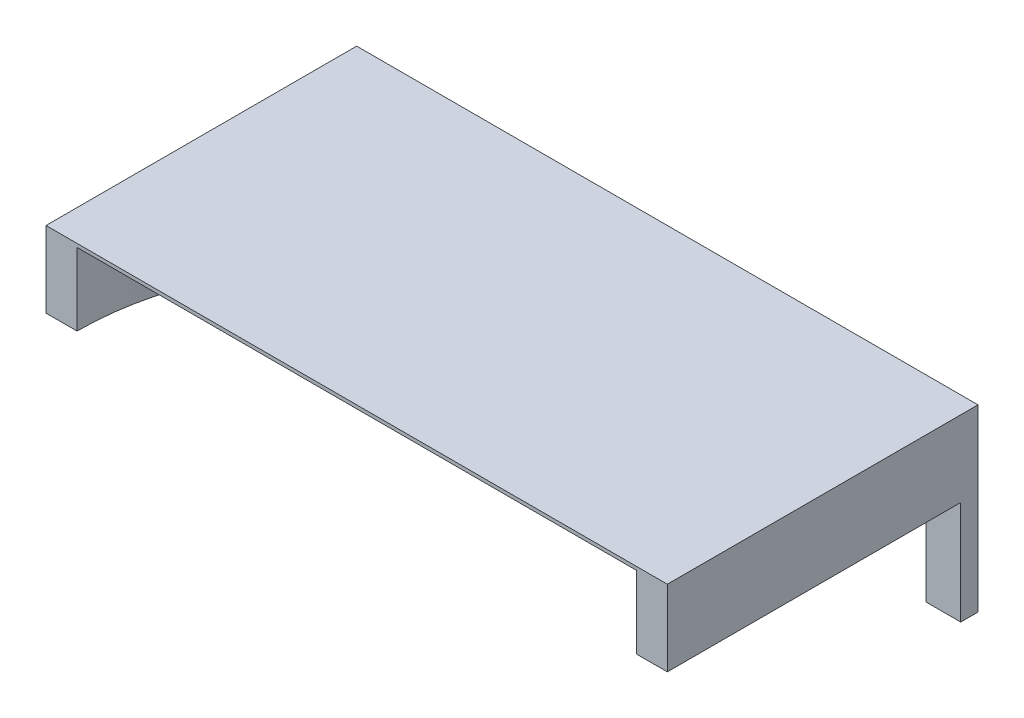
SolidWorks part; units mm, degrees
ref_plane "Спереди" through (0, 0, 0) normal (0, 0, 1) x (1, 0, 0)
ref_plane "Сверху" through (0, 0, 0) normal (0, 1, 0) x (1, 0, 0)
ref_plane "Справа" through (0, 0, 0) normal (1, 0, 0) x (0, 0, -1)
sketch "Эскиз1" plane through (0, 0, 0) normal (0, 1, 0) x (-1, 0, 0)
  line L1 (-90, 0) -> (90, 0)
  line L3 (-81, 90) -> (-90, 90)
  line L4 (-90, 90) -> (-90, 0)
  line L5 (81, 90) -> (90, 90)
  line L6 (90, 90) -> (90, 0)
  arc A1 (-81, 90) -> (81, 90) centre (0, 90) ccw
  point P1 (0, 0)
  point P4 (-90.9511, -95.2829)
  point P12 (92.9028, -95.2829)
  dimension "D3" = 81
  dimension "D1" = 90
  dimension "D2" = 180
extrude "Бобышка-Вытянуть1" add sketch "Эскиз1" along normal blind 22 contours L4 L1 L6 L5 A1 L3
sketch "Эскиз2" plane through (0, 22, 0) normal (0, 1, 0) x (1, 0, 0)
  line L1 (-90, 0) -> (90, 0)
  line L2 (-90, 0) -> (-90, -90)
  line L3 (-90, -90) -> (90, -90)
  line L4 (90, 0) -> (90, -90)
extrude "Бобышка-Вытянуть2" add sketch "Эскиз2" against normal blind 1
sketch "Эскиз3" plane through (0, 0, 0) normal (0, -1, 0) x (1, 0, 0)
  line L1 (-90, 0) -> (-80, 0)
  line L2 (-90, 0) -> (-90, 5)
  line L3 (-90, 5) -> (-80, 5)
  line L4 (-80, 0) -> (-80, 5)
  line L5 (90, 0) -> (80, 0)
  line L6 (90, 0) -> (90, 5)
  line L7 (90, 5) -> (80, 5)
  line L8 (80, 0) -> (80, 5)
  dimension "D1" = 10
  dimension "D2" = 5
  dimension "D3" = 10
  dimension "D4" = 5
extrude "Бобышка-Вытянуть3" add sketch "Эскиз3" along normal blind 30
fillet "Скругление1" radius 10 2 edges at (80, 0, 2.5) (-80, 0, 2.5)
